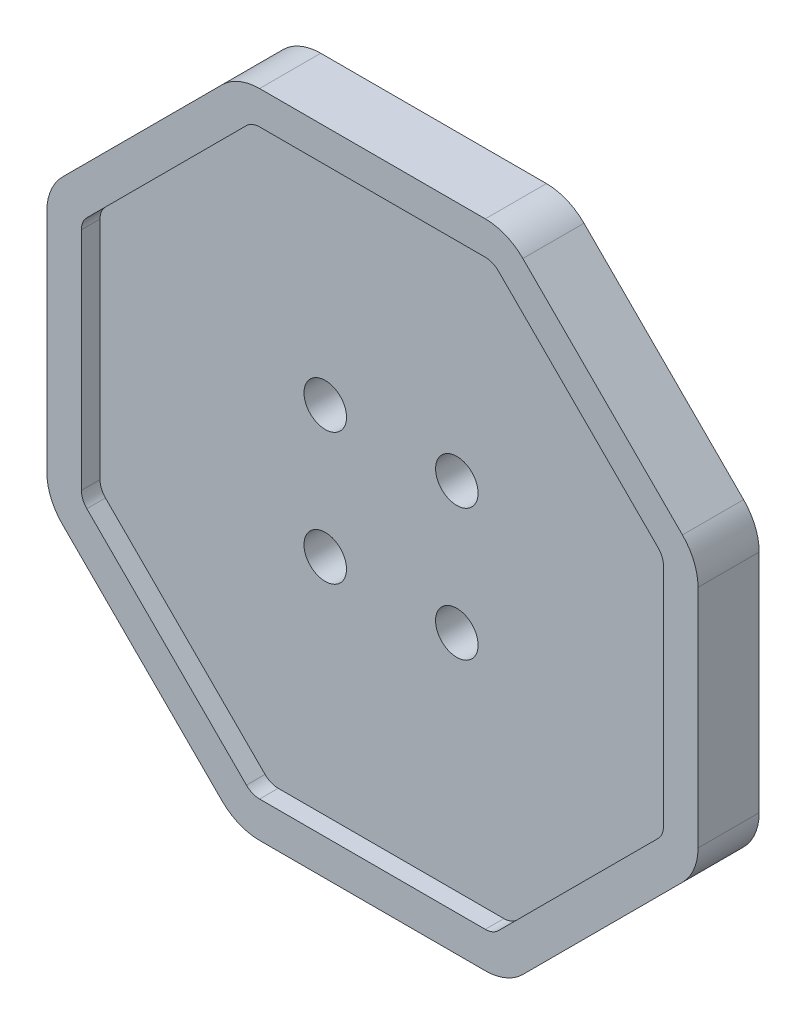
SolidWorks part; units mm, degrees
ref_plane "Front Plane" through (0, 0, 0) normal (0, 0, 1) x (1, 0, 0)
ref_plane "Top Plane" through (0, 0, 0) normal (0, 1, 0) x (1, 0, 0)
ref_plane "Right Plane" through (0, 0, 0) normal (1, 0, 0) x (0, 0, -1)
sketch "Sketch1" plane through (0, 0, 0) normal (0, 0, 1) x (1, 0, 0)
  line L1 (-4.9497, 4.9497) -> (4.9497, 4.9497) construction
  line L2 (-4.9497, 4.9497) -> (-4.9497, -4.9497) construction
  line L3 (-4.9497, -4.9497) -> (4.9497, -4.9497) construction
  line L4 (4.9497, 4.9497) -> (4.9497, -4.9497) construction
  line L5 (-4.9497, 4.9497) -> (4.9497, -4.9497) construction
  line L6 (-4.9497, -4.9497) -> (4.9497, 4.9497) construction
  line L8 (-11.3198, 23.3284) -> (-23.3284, 11.3198)
  line L9 (-24.5, 8.4914) -> (-24.5, -8.4914)
  line L10 (-23.3284, -11.3198) -> (-11.3198, -23.3284)
  line L11 (-8.4914, -24.5) -> (8.4914, -24.5)
  line L12 (11.3198, -23.3284) -> (23.3284, -11.3198)
  line L13 (24.5, -8.4914) -> (24.5, 8.4914)
  line L14 (23.3284, 11.3198) -> (11.3198, 23.3284)
  line L15 (8.4914, 24.5) -> (-8.4914, 24.5)
  circle A1 centre (-4.9497, 4.9497) radius 1.6
  circle A2 centre (4.9497, 4.9497) radius 1.6
  circle A3 centre (4.9497, -4.9497) radius 1.6
  circle A4 centre (-4.9497, -4.9497) radius 1.6
  circle A5 centre (0, 0) radius 24.5 construction
  arc A6 (11.3198, 23.3284) -> (8.4914, 24.5) centre (8.4914, 20.5) ccw
  arc A7 (24.5, 8.4914) -> (23.3284, 11.3198) centre (20.5, 8.4914) ccw
  arc A8 (23.3284, -11.3198) -> (24.5, -8.4914) centre (20.5, -8.4914) ccw
  arc A9 (8.4914, -24.5) -> (11.3198, -23.3284) centre (8.4914, -20.5) ccw
  arc A10 (-11.3198, -23.3284) -> (-8.4914, -24.5) centre (-8.4914, -20.5) ccw
  arc A11 (-24.5, -8.4914) -> (-23.3284, -11.3198) centre (-20.5, -8.4914) ccw
  arc A12 (-23.3284, 11.3198) -> (-24.5, 8.4914) centre (-20.5, 8.4914) ccw
  arc A13 (-11.3198, 23.3284) -> (-8.4914, 24.5) centre (-8.4914, 20.5) cw
  point P1 (0, 0)
  point P2 (0, 0)
  dimension "D1" = 3.2
  dimension "D3" = 49
  dimension "D4" = 4
  dimension "D2" = 14
extrude "Boss-Extrude1" add sketch "Sketch1" along normal blind 4.6
sketch "Sketch3" plane through (0, 0, 4.6) normal (0, 0, 1) x (1, 0, 0)
  line L0 (8.4914, 24.5) -> (-8.4914, 24.5) construction
  line L9 (8.4914, 22) -> (-8.4914, 22)
  line L11 (-9.4813, 21.5899) -> (-21.4899, 9.5813)
  line L13 (-21.9, 8.5914) -> (-21.9, -8.3914)
  line L20 (-21.4899, -9.3813) -> (-9.4813, -21.3899)
  line L22 (-8.4914, -21.8) -> (8.4914, -21.8)
  line L24 (9.4813, -21.3899) -> (21.4899, -9.3813)
  line L26 (21.9, -8.3914) -> (21.9, 8.5914)
  line L28 (21.4899, 9.5813) -> (9.4813, 21.5899)
  arc A9 (9.4813, 21.5899) -> (8.4914, 22) centre (8.4914, 20.6) ccw
  arc A11 (21.9, 8.5914) -> (21.4899, 9.5813) centre (20.5, 8.5914) ccw
  arc A13 (-8.4914, 22) -> (-9.4813, 21.5899) centre (-8.4914, 20.6) ccw
  arc A20 (-21.4899, 9.5813) -> (-21.9, 8.5914) centre (-20.5, 8.5914) ccw
  arc A22 (-21.9, -8.3914) -> (-21.4899, -9.3813) centre (-20.5, -8.3914) ccw
  arc A24 (-9.4813, -21.3899) -> (-8.4914, -21.8) centre (-8.4914, -20.4) ccw
  arc A26 (8.4914, -21.8) -> (9.4813, -21.3899) centre (8.4914, -20.4) ccw
  arc A28 (21.4899, -9.3813) -> (21.9, -8.3914) centre (20.5, -8.3914) ccw
  dimension "D1" = 2.5
extrude "Cut-Extrude2" cut sketch "Sketch3" against normal blind 1.4
